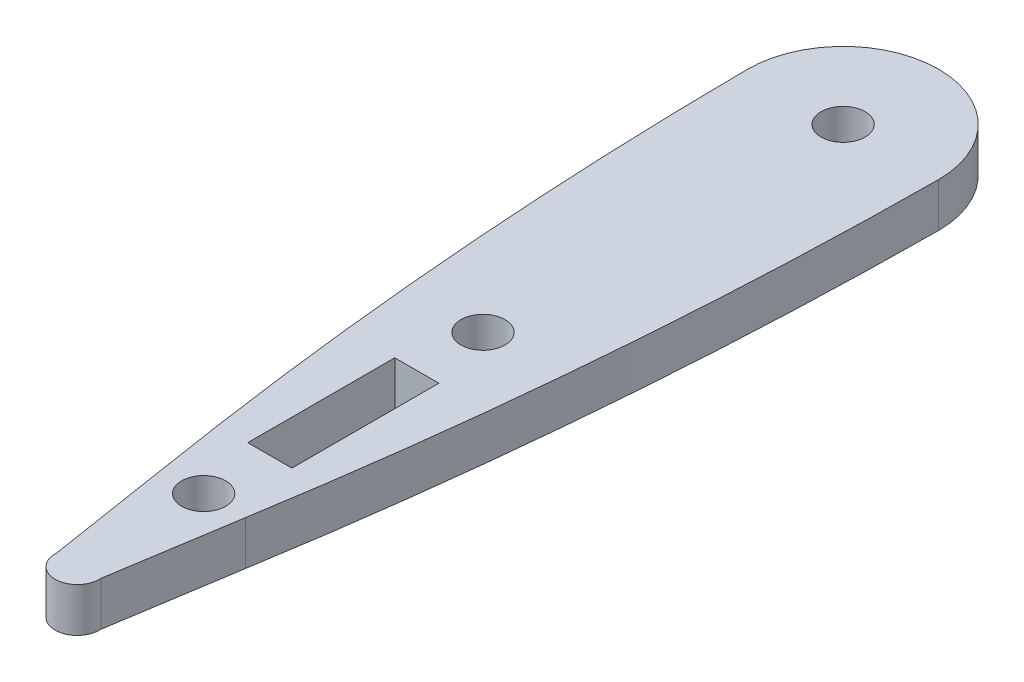
SolidWorks part; units mm, degrees
material "Cedro"
ref_plane "Plano frontal" through (0, 0, 0) normal (0, 0, 1) x (1, 0, 0)
ref_plane "Plano superior" through (0, 0, 0) normal (0, 1, 0) x (1, 0, 0)
ref_plane "Plano direito" through (0, 0, 0) normal (1, 0, 0) x (0, 0, -1)
sketch "Esboço1" plane through (0, 0, 0) normal (0, 1, 0) x (1, 0, 0)
  line L0 (0, -10.9549) -> (1.5, -10.9549)
  line L1 (1.5, -10.9549) -> (1.5, -20.9549)
  line L2 (1.5, -20.9549) -> (0, -20.9549)
  line L3 (0, -10.9549) -> (-1.5, -10.9549)
  line L4 (-1.5, -10.9549) -> (-1.5, -20.9549)
  line L5 (-1.5, -20.9549) -> (0, -20.9549)
  line L10 (-1.5, -33.9549) -> (-2.839, -25.4549)
  line L11 (1.5, -33.9549) -> (2.839, -25.4549)
  arc A0 (6.4994, 17.9589) -> (-6.4994, 17.9589) centre (0, 18.0451) ccw
  circle A1 centre (0, -6.4549) radius 1.5
  circle A2 centre (0, -25.4549) radius 1.5
  arc A6 (-2.839, -25.4549) -> (-6.5, 18.0451) centre (275.4609, 19.8713) cw
  arc A7 (2.839, -25.4549) -> (6.5, 18.0451) centre (-275.4609, 19.8713) ccw
  arc A8 (-1.5, -33.9549) -> (1.5, -33.9549) centre (0, -34.0536) ccw
  circle A9 centre (0, 18.0451) radius 1.5
extrude "Ressalto-extrusão1" add sketch "Esboço1" along normal blind 3 contours L10 A8 L11 A7 A0 A6 A9 A1 A2
